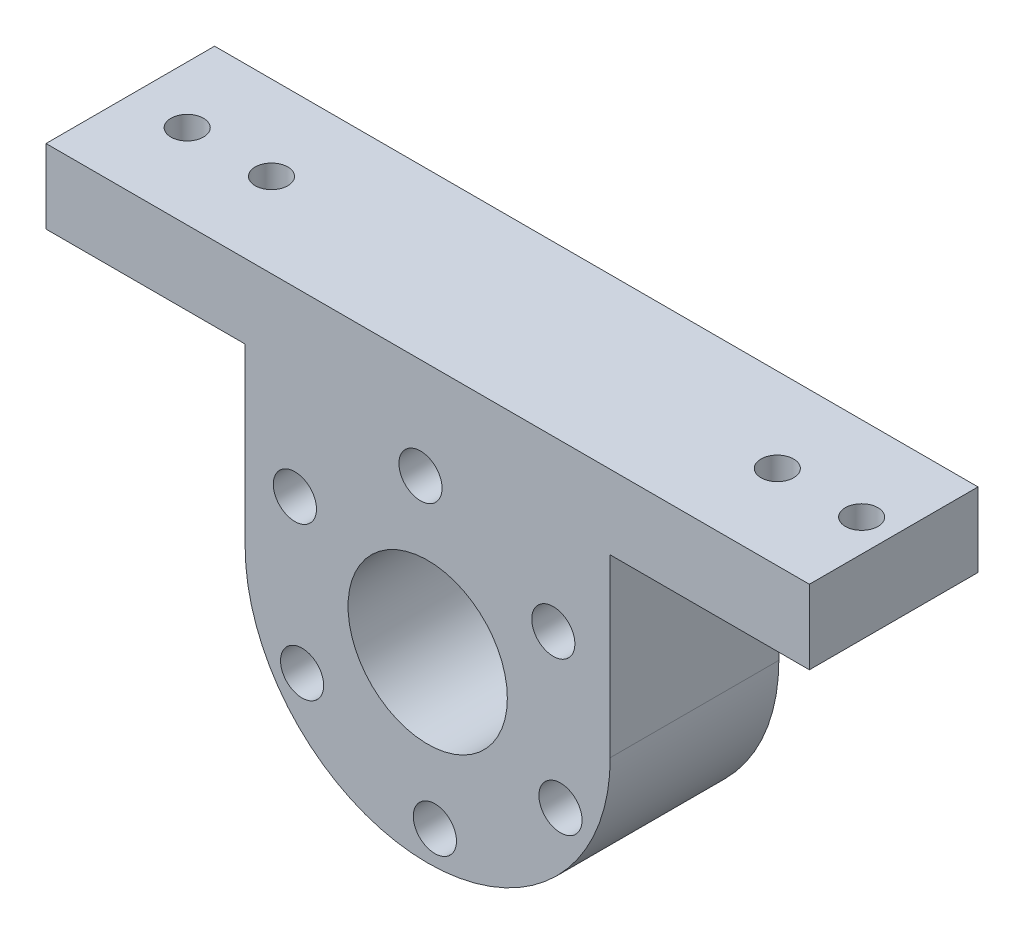
SolidWorks part; units mm, degrees
ref_plane "Front Plane" through (0, 0, 0) normal (0, 0, 1) x (1, 0, 0)
ref_plane "Top Plane" through (0, 0, 0) normal (0, 1, 0) x (1, 0, 0)
ref_plane "Right Plane" through (0, 0, 0) normal (1, 0, 0) x (0, 0, -1)
sketch "Sketch1" plane through (0, 0, 0) normal (0, 0, 1) x (1, 0, 0)
  line L0 (-85, -37.625) -> (-85, 0)
  line L2 (-85, 0) -> (-30, 0)
  line L3 (-30, 0) -> (-30, -37.625)
  line L4 (-85, -11.1675) -> (-115, -11.1675)
  line L5 (-115, -11.1675) -> (-115, 0)
  line L6 (-115, 0) -> (-85, 0)
  line L7 (-30, -11.1675) -> (0, -11.1675)
  line L8 (0, -11.1675) -> (0, 0)
  line L9 (0, 0) -> (-30, 0)
  line L10 (-115, -11.1675) -> (-85, -37.625)
  line L11 (-30, -37.625) -> (0, -11.1675)
  line L12 (-115, 0) -> (-85, 0)
  line L13 (-30, 0) -> (0, 0)
  circle A1 centre (-57.5, -37.625) radius 27.5
  circle A9 centre (-57.5, -37.625) radius 12
  circle A10 centre (-77.5045, -27.326) radius 3.25
  circle A11 centre (-76.4214, -49.7999) radius 3.25
  circle A12 centre (-56.4169, -60.0989) radius 3.25
  circle A13 centre (-37.4955, -47.924) radius 3.25
  circle A14 centre (-38.5786, -25.4501) radius 3.25
  circle A15 centre (-58.5831, -15.1511) radius 3.25
  point P1 (0, 0)
  dimension "D3" = 6.5
  dimension "D4" = 24
  dimension "D5" = 55
  dimension "D1" = 30
  dimension "D2" = 40
  dimension "D6" = 1.0831
  dimension "D7" = 18.9214
  dimension "D8" = 20.0045
  dimension "D9" = 1.0831
  dimension "D10" = 18.9214
  dimension "D11" = 20.0045
  dimension "D12" = 10.299
  dimension "D13" = 12.1749
  dimension "D14" = 22.4739
  dimension "D15" = 37.625
  dimension "D16" = 10.299
  dimension "D17" = 12.1749
  dimension "D18" = 22.4739
extrude "Boss-Extrude1" add sketch "Sketch1" along normal blind 25.4 contours L6 L5 L4 L0 | A1 L3 L2 L0 | A1 A15 A14 A13 A12 A11 A10 A9 | L8 L9 L3 L7
sketch "Sketch2" plane through (0, 0, 0) normal (0, 1, 0) x (1, 0, 0)
  circle A4 centre (-93.73, -12.7) radius 2.4574
  circle A5 centre (-106.43, -12.7) radius 2.4574
  circle A6 centre (-17.53, -12.7) radius 2.4574
  circle A7 centre (-4.83, -12.7) radius 2.4574
extrude "Cut-Extrude1" cut sketch "Sketch2" against normal blind 31
